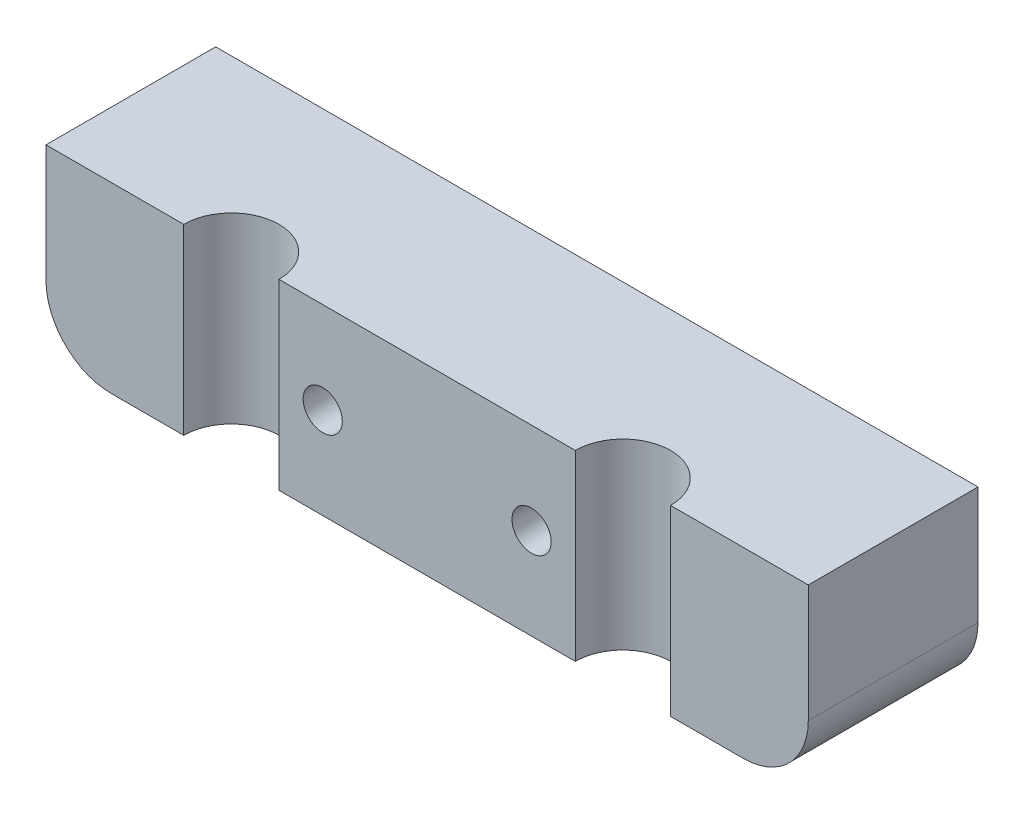
SolidWorks part; units mm, degrees
material "ABS"
ref_plane "Front" through (0, 0, 0) normal (0, 0, 1) x (1, 0, 0)
ref_plane "Top" through (0, 0, 0) normal (0, 1, 0) x (1, 0, 0)
ref_plane "Right" through (0, 0, 0) normal (1, 0, 0) x (0, 0, -1)
sketch "Эскиз1" plane through (0, 0, 0) normal (0, 0, 1) x (1, 0, 0)
  line L1 (-29.2, -7) -> (29.2, -7)
  line L2 (-29.2, -7) -> (-29.2, 7)
  line L3 (-29.2, 7) -> (29.2, 7)
  line L4 (29.2, -7) -> (29.2, 7)
  line L5 (-29.2, -7) -> (29.2, 7) construction
  line L6 (-29.2, 7) -> (29.2, -7) construction
  point P0 (0, 0)
  dimension "D1" = 58.4
  dimension "D2" = 14
extrude "Бобышка-Вытянуть1" add sketch "Эскиз1" along normal blind 13
sketch "Эскиз2" plane through (0, 0, 13) normal (0, 0, 1) x (1, 0, 0)
  line L0 (-29.2, 0) -> (29.2, 0) construction
  line L1 (-29.2, 7) -> (-29.2, -7) construction
  line L2 (29.2, -7) -> (29.2, 7) construction
  line L3 (0, 7) -> (0, 0) construction
  line L4 (29.2, 7) -> (-29.2, 7) construction
  circle A0 centre (-8, 0) radius 1.5
  circle A1 centre (8, 0) radius 1.5
  dimension "D1" = 8
extrude "Вырез-Вытянуть1" cut sketch "Эскиз2" against normal up to next
sketch "Эскиз3" plane through (0, 7, 0) normal (0, 1, 0) x (1, 0, 0)
  line L0 (0, 0) -> (0, -13) construction
  line L1 (29.2, 0) -> (-29.2, 0) construction
  line L2 (29.2, -13) -> (-29.2, -13) construction
  line L3 (0, -13) -> (-15, -13) construction
  circle A0 centre (-15, -13) radius 3.65
  circle A1 centre (15, -13) radius 3.65
  dimension "D2" = 7.3
  dimension "D3" = 13
  dimension "D1" = 15
extrude "Вырез-Вытянуть2" cut sketch "Эскиз3" against normal up to next
sketch "Эскиз4" plane through (0, 0, 0) normal (0, 0, -1) x (-1, 0, 0)
  circle A0 centre (-8, 0) radius 3
  circle A1 centre (8, 0) radius 3
extrude "Вырез-Вытянуть3" cut sketch "Эскиз4" against normal blind 3.8
fillet "Скругление1" radius 5 2 edges at (-29.2, -7, 6.5) (29.2, -7, 6.5)
